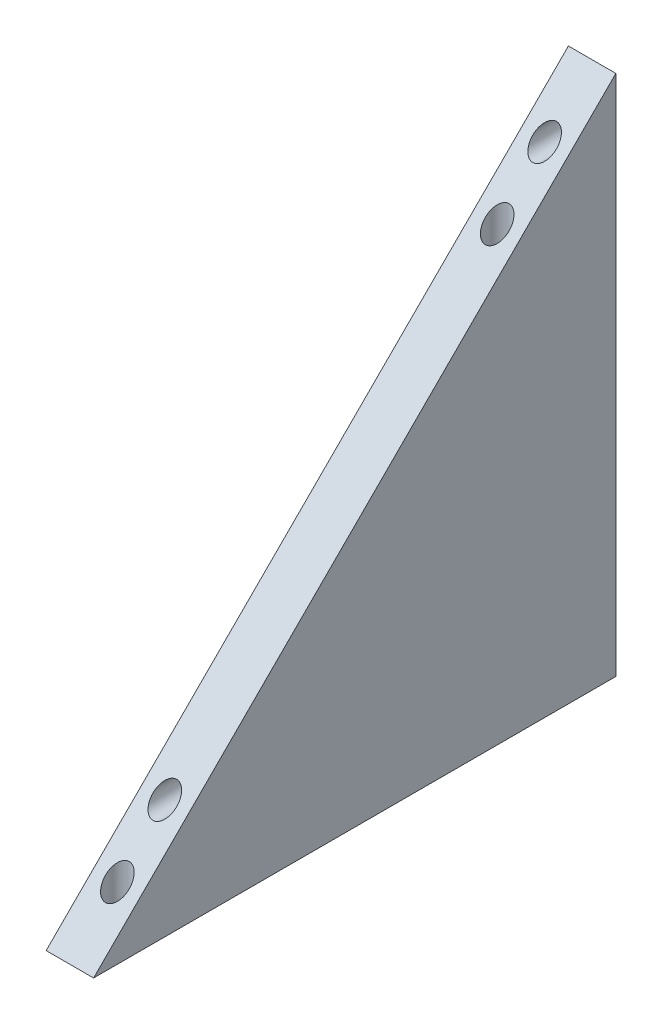
SolidWorks part; units mm, degrees
ref_plane "Front Plane" through (0, 0, 0) normal (0, 0, 1) x (1, 0, 0)
ref_plane "Top Plane" through (0, 0, 0) normal (0, 1, 0) x (1, 0, 0)
ref_plane "Right Plane" through (0, 0, 0) normal (1, 0, 0) x (0, 0, -1)
sketch "Sketch1" plane through (0, 0, 0) normal (1, 0, 0) x (0, 0, -1)
  line L0 (-88, 0) -> (0, 0)
  line L1 (55, 0) -> (-55, 0) construction
  line L2 (0, 0) -> (0, 88)
  line L3 (0, 55) -> (0, -55) construction
  line L4 (0, 88) -> (-88, 0)
  dimension "D1" = 88
  dimension "D2" = 88
extrude "Boss-Extrude1" add sketch "Sketch1" along normal blind 8
sketch "Sketch2" plane through (0, 0, 0) normal (0, 1, 0) x (1, 0, 0)
  line L0 (4, -1056) -> (4, 48944) construction
  line L1 (8, -88) -> (0, -88) construction
  line L2 (-4.4, 0) -> (4.4, 0) construction
  circle A0 centre (4, -16) radius 2
  circle A1 centre (4, -80) radius 2
  point P5 (4, -88)
  dimension "D1" = 4
  dimension "D2" = 16
  dimension "D3" = 64
extrude "Cut-Extrude1" cut sketch "Sketch2" along normal through all
sketch "Sketch3" plane through (0, 0, 0) normal (0, 0, 1) x (1, 0, 0)
  line L0 (4, -944) -> (4, 49056) construction
  line L1 (8, 88) -> (0, 88) construction
  line L2 (4.4, 0) -> (-4.4, 0) construction
  circle A0 centre (4, 16) radius 2
  circle A1 centre (4, 80) radius 2
  point P5 (4, 88)
  dimension "D1" = 4
  dimension "D2" = 16
  dimension "D3" = 64
extrude "Cut-Extrude2" cut sketch "Sketch3" along normal through all
equation "\"D1@Sketch1\"=16+64+8"
equation "\"D2@Sketch1\"=\"D1@Sketch1\""
